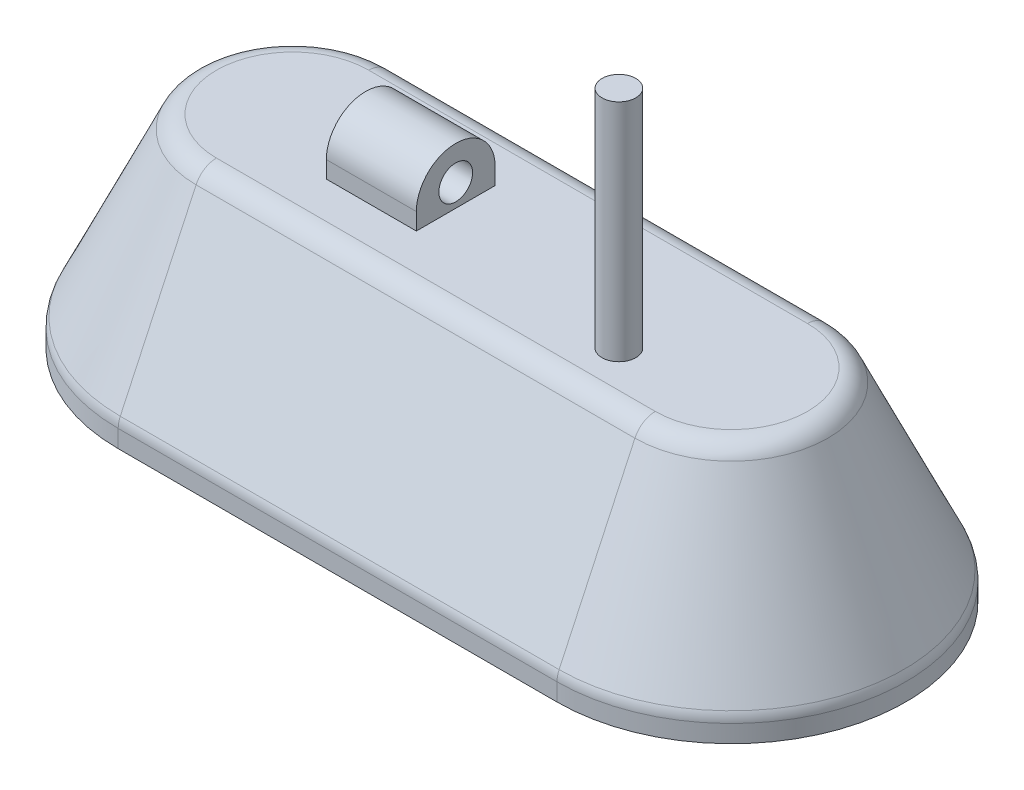
SolidWorks part; units mm, degrees
ref_plane "Front Plane" through (0, 0, 0) normal (0, 0, 1) x (1, 0, 0)
ref_plane "Top Plane" through (0, 0, 0) normal (0, 1, 0) x (1, 0, 0)
ref_plane "Right Plane" through (0, 0, 0) normal (1, 0, 0) x (0, 0, -1)
sketch "Sketch1" plane through (0, 0, 0) normal (0, 1, 0) x (1, 0, 0)
  line L0 (0, 0) -> (-39, 0)
  line L2 (-39, 31) -> (0, 31)
  arc A0 (0, 31) -> (0, 0) centre (0, 15.5) cw
  arc A1 (-39, 31) -> (-39, 0) centre (-39, 15.5) ccw
  point P7 (-54.5, 15.5)
  point P8 (15.5, 15.5)
  dimension "D1" = 15.5
  dimension "D2" = 70
extrude "Boss-Extrude1" add sketch "Sketch1" along normal blind 18
sketch "Sketch2" plane through (0, 18, 0) normal (0, 1, 0) x (1, 0, 0)
  line L0 (-39, 0) -> (0, 0) construction
  circle A0 centre (-6.5, 12) radius 1.5
  arc A1 (0, 0) -> (0, 31) centre (0, 15.5) ccw construction
  point P5 (15.5, 15.5)
  dimension "D1" = 22
  dimension "D2" = 12
  dimension "D3" = 3
extrude "Boss-Extrude2" add sketch "Sketch2" along normal blind 20
sketch "Sketch3" plane through (0, 18, 0) normal (0, 1, 0) x (1, 0, 0)
  line L0 (-32.5, 12) -> (-24.5, 12)
  line L1 (-24.5, 12) -> (-24.5, 19)
  line L2 (-24.5, 19) -> (-32.5, 19)
  line L3 (-32.5, 19) -> (-32.5, 12)
  line L4 (-39, 0) -> (0, 0) construction
  arc A0 (-39, 31) -> (-39, 0) centre (-39, 15.5) ccw construction
  point P7 (-54.5, 15.5)
  point P8 (-32.5, 15.5)
  dimension "D1" = 30
  dimension "D2" = 8
  dimension "D3" = 7
  dimension "D4" = 15.5
extrude "Boss-Extrude3" add sketch "Sketch3" along normal blind 5
sketch "Sketch4" plane through (-32.5, 0, 0) normal (-1, 0, 0) x (0, 0, 1)
  line L6 (-19, 23) -> (-12, 23) construction
  line L7 (-19, 19.5) -> (-19, 26.5509)
  line L8 (-19, 26.5509) -> (-12, 26.5509)
  line L9 (-12, 26.5509) -> (-12, 19.5)
  arc A1 (-19, 19.5) -> (-12, 19.5) centre (-15.5, 19.5) cw
  circle A2 centre (-15.5, 20) radius 1.5
  dimension "D1" = 3.5
  dimension "D2" = 3
  dimension "D3" = 0.5
extrude "Cut-Extrude1" cut sketch "Sketch4" against normal blind 10
chamfer "Chamfer1" distance 16 angle 25 4 edges at (-19.5, 18, 0) (15.5, 18, -15.5) (-54.5, 18, -15.5) (-19.5, 18, -31)
fillet "Fillet3" radius 2 8 edges at (-54.5, 2, -15.5) (-19.5, 2, 0) (15.5, 2, -15.5) (8.0391, 18, -15.5) (-19.5, 18, -7.4609) (-47.0391, 18, -15.5) (-19.5, 2, -31) (-19.5, 18, -23.5391)
